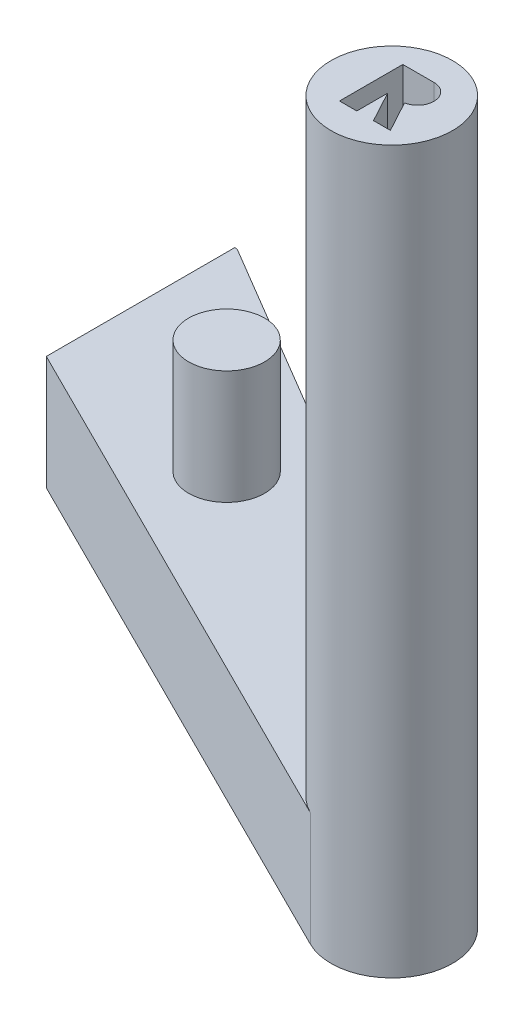
SolidWorks part; units mm, degrees
ref_plane "Front Plane" through (0, 0, 0) normal (0, 0, 1) x (1, 0, 0)
ref_plane "Top Plane" through (0, 0, 0) normal (0, 1, 0) x (1, 0, 0)
ref_plane "Right Plane" through (0, 0, 0) normal (1, 0, 0) x (0, 0, -1)
sketch "Sketch1" plane through (0, 0, 0) normal (0, 1, 0) x (1, 0, 0)
  circle A0 centre (0, 0) radius 8
  dimension "D1" = 16
extrude "Boss-Extrude1" add sketch "Sketch1" along normal blind 95 contours A0
sketch "Sketch2" plane through (0, 0, 0) normal (0, -1, 0) x (1, 0, 0)
  circle A0 centre (0, 0) radius 4
extrude "Cut-Extrude1" cut sketch "Sketch2" against normal blind 45
sketch "Sketch4" plane through (0, 95, 0) normal (0, 1, 0) x (1, 0, 0)
  line L0 (-2.827, 4.2786) -> (-0.5476, 4.2786)
  line L1 (-2.827, 4.2786) -> (-2.827, 0)
  line L2 (-0.5476, 4.2786) -> (-0.5476, 0)
  line L3 (-2.827, 0) -> (-0.5476, 0)
  line L4 (0, 6.5797) -> (0, -7.2671) construction
  line L5 (-9.0666, 0) -> (13.0713, 0) construction
  line L6 (-0.5476, 4.2786) -> (1.2753, 4.2786)
  line L15 (-0.5476, 0) -> (1.6758, 0)
  line L16 (-0.5476, 0) -> (1.6537, -4.0629)
  line L17 (1.6758, 0) -> (3.8772, -4.0629)
  line L18 (1.6537, -4.0629) -> (3.8772, -4.0629)
  line L19 (-2.827, -4.0629) -> (3.8772, -4.0629) construction
  line L20 (-2.827, 0) -> (-0.5476, 0)
  line L21 (-2.827, 0) -> (-2.827, -4.0629)
  line L22 (-2.827, -4.0629) -> (-0.5476, -4.0629)
  line L23 (-0.5476, 0) -> (-0.5476, -4.0629)
  arc A0 (1.2753, 4.2786) -> (1.6758, 0) centre (1.2753, 2.1206) cw
  point P12 (-0.5476, 0)
  dimension "D8" = 2.158
  dimension "D1" = 4.2786
  dimension "D2" = 4.0629
  dimension "D3" = 2.2793
  dimension "D4" = 2.2234
  dimension "D5" = 1.8229
  dimension "D6" = 28.45
  dimension "D7" = 0.5476
extrude "Cut-Extrude2" cut sketch "Sketch4" against normal blind 40
sketch "Sketch5" plane through (0, 0, 0) normal (0, 1, 0) x (1, 0, 0)
  line L0 (0, 0) -> (-37.2689, 0) construction
  line L1 (0, 0) -> (-75.0017, 39.9967) construction
  line L2 (-75.0017, 52.4967) -> (-75.0017, 27.4967)
  line L3 (-73.0017, 52.4967) -> (-73.0017, 27.4967)
  line L4 (-73.0017, 27.4967) -> (-3.5728, -7.1579)
  line L5 (-73.0017, 52.4967) -> (4.0743, 6.8848)
  circle A0 centre (-75.0017, 39.9967) radius 12.5
  circle A1 centre (0, 0) radius 8 construction
  circle A2 centre (0, 0) radius 8
  dimension "D3" = 25
  dimension "D1" = 28.07
  dimension "D2" = 85
  dimension "D4" = 2
extrude "Boss-Extrude2" add sketch "Sketch5" along normal blind 15 contours A2 L5 A0 L3 L4 | L3 A0 L5
sketch "Sketch6" plane through (0, 15, 0) normal (0, 1, 0) x (1, 0, 0)
  line L2 (-73.0017, 39.9162) -> (0, 0) construction
  line L3 (-73.0017, 52.3357) -> (-73.0017, 27.4967) construction
  circle A0 centre (-48.0017, 26.2466) radius 5
  circle A1 centre (0, 0) radius 8
  dimension "D1" = 10
  dimension "D2" = 25
extrude "Boss-Extrude3" add sketch "Sketch6" along normal blind 15 contours A0
sketch "Sketch7" plane through (0, 45, 0) normal (0, -1, 0) x (1, 0, 0)
  line L0 (1.7288, -3.7907) -> (0, 0) construction
  line L1 (0, 0) -> (-3.6544, 8.0127) construction
ref_plane "Plane1" through (0, 0, 0) normal (0.9098, 0, 0.415) x (-0.415, 0, 0.9098)
sketch "Sketch8" plane through (0, 0, 0) normal (0.9098, 0, 0.415) x (-0.415, 0, 0.9098)
  line L0 (0, -45) -> (-4.1664, -45)
  line L1 (-4.1664, -45) -> (0, -52.2164)
  line L2 (0, -52.2164) -> (0, -45)
  dimension "D1" = 30
revolve "Cut-Revolve1" cut sketch "Sketch8" angle 360 about L2
